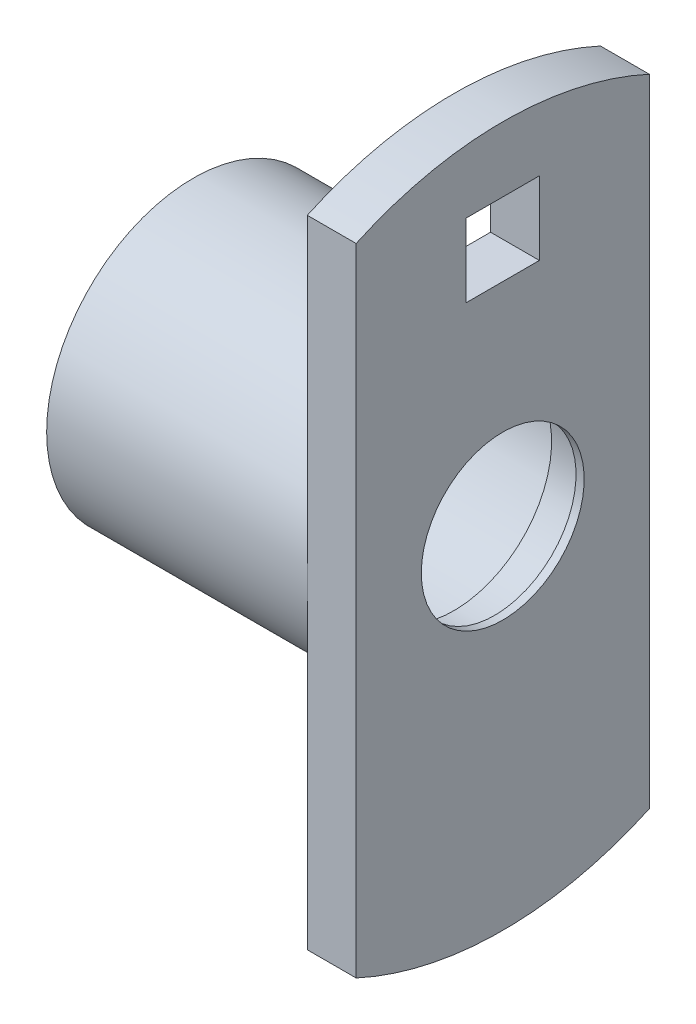
SolidWorks part; units mm, degrees
ref_plane "Front Plane" through (0, 0, 0) normal (0, 0, 1) x (1, 0, 0)
ref_plane "Top Plane" through (0, 0, 0) normal (0, 1, 0) x (1, 0, 0)
ref_plane "Right Plane" through (0, 0, 0) normal (1, 0, 0) x (0, 0, -1)
sketch "Sketch3" plane through (0, 0, 0) normal (0, 0, 1) x (1, 0, 0)
  line L0 (-15.4261, 0) -> (15.4261, 0) construction
  line L1 (0, -10.1639) -> (0, 10.1639) construction
sketch "Sketch1" plane through (0, 0, 0) normal (0, 0, 1) x (1, 0, 0)
  line L0 (-42.8096, 0) -> (42.8096, 0) construction
  line L1 (-1, 12) -> (-6, 12)
  line L2 (-6, 12) -> (-6, 16)
  line L3 (-6, 16) -> (-38, 16)
  line L4 (-38, 16) -> (-38, 18)
  line L6 (0, 43) -> (0, 10)
  line L9 (0, 10) -> (-1, 10)
  line L10 (-1, 10) -> (-1, 12)
  line L11 (-38, 18) -> (-6, 18)
  line L12 (-6, 18) -> (-6, 43)
  line L13 (-6, 43) -> (0, 43)
  point P3 (0, 0)
  dimension "D1" = 2
  dimension "D2" = 6
  dimension "D3" = 5
  dimension "D4" = 24
  dimension "D5" = 32
  dimension "D6" = 2
  dimension "D7" = 86
  dimension "D8" = 6
  dimension "D9" = 32
revolve "Revolve1" add sketch "Sketch1" angle 360 about L0
sketch "Sketch2" plane through (0, 0, 0) normal (1, 0, 0) x (0, 0, -1)
  line L0 (0, 43) -> (0, 18) construction
  line L3 (0, 43) -> (0, 10) construction
  line L4 (-18, 39.0512) -> (-18, -39.0512)
  line L5 (-4.5, 26) -> (4.5, 26)
  line L6 (-4.5, 26) -> (-4.5, 35)
  line L7 (-4.5, 35) -> (4.5, 35)
  line L8 (4.5, 26) -> (4.5, 35)
  line L9 (-4.5, 26) -> (4.5, 35) construction
  line L10 (-4.5, 35) -> (4.5, 26) construction
  line L11 (18, -39.0512) -> (18, 39.0512)
  circle A0 centre (0, 0) radius 43 construction
  circle A1 centre (0, 0) radius 18 construction
  circle A3 centre (0, 0) radius 43
  point P2 (0, 0)
  point P3 (0, 30.5)
  point P5 (0, 30.5)
  dimension "D1" = 9
extrude "Cut-Extrude1" cut sketch "Sketch2" against normal up to surface (6 mm away) contours L4 A3 | L5 L8 L7 L6 | L11 A3 up to face at (-6, 0, 18)
